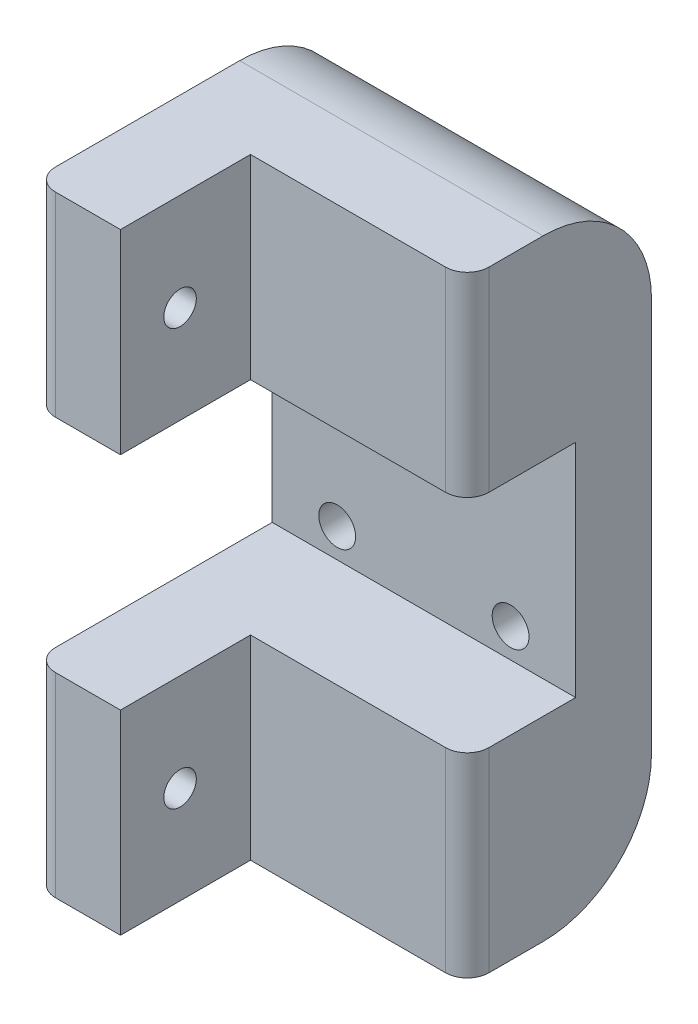
SolidWorks part; units mm, degrees
ref_plane "前视基准面" through (0, 0, 0) normal (0, 0, 1) x (1, 0, 0)
ref_plane "上视基准面" through (0, 0, 0) normal (0, 1, 0) x (1, 0, 0)
ref_plane "右视基准面" through (0, 0, 0) normal (1, 0, 0) x (0, 0, -1)
sketch "草图1" plane through (0, 0, 0) normal (0, 0, 1) x (1, 0, 0)
  line L0 (0, 10.2) -> (30.5146, 10.2) construction
  line L1 (0, 0) -> (28, 0)
  line L2 (0, 0) -> (0, 20.4)
  line L3 (0, 20.4) -> (28, 20.4)
  line L4 (28, 0) -> (28, 20.4)
  line L5 (14, 0) -> (14, 23.8406) construction
  circle A0 centre (6, 2.7) radius 1.5
  circle A1 centre (22, 2.7) radius 1.5
  circle A2 centre (22, 17.7) radius 1.5
  circle A3 centre (6, 17.7) radius 1.5
  point P17 (0, 0)
  point P18 (14, 0)
  dimension "D1" = 3
  dimension "D4" = 20.4
  dimension "D5" = 28
  dimension "D2" = 2
  dimension "D3" = 2
sketch "草图2" plane through (0, 0, 0) normal (0, 0, 1) x (1, 0, 0)
  line L1 (0, 0) -> (28, 0)
  line L2 (0, 0) -> (0, 20.4)
  line L3 (0, 20.4) -> (28, 20.4)
  line L4 (28, 0) -> (28, 20.4)
extrude "凸台-拉伸2" add sketch "草图2" along normal blind 7
sketch "草图5" plane through (0, 20.4, 0) normal (0, 1, 0) x (1, 0, 0)
  line L1 (0, 0) -> (28, 0)
  line L2 (0, 0) -> (0, -17)
  line L3 (0, -17) -> (28, -17)
  line L4 (28, 0) -> (28, -17)
  dimension "D1" = 17
  dimension "D2" = 28
extrude "凸台-拉伸3" add sketch "草图5" along normal blind 18
sketch "草图6" plane through (0, 0, 0) normal (0, -1, 0) x (1, 0, 0)
  line L0 (0, 0) -> (28, 0) construction
  line L1 (0, 17) -> (28, 17)
  line L2 (0, 17) -> (0, 0)
  line L3 (0, 0) -> (28, 0)
  line L4 (28, 17) -> (28, 0)
  dimension "D1" = 28
extrude "凸台-拉伸4" add sketch "草图6" along normal blind 18
hole_wizard "打孔尺寸(%根据十字)槽半沉头木螺钉的类型2" positions "草图7" profile "草图8" countersink size "M3" standard "GB" end condition through all
sketch "草图7" plane through (0, 0, 0) normal (0, 0, -1) x (-1, 0, 0)
  point P0 (-22, 17.7)
  point P3 (-6, 17.7)
  point P6 (-6, 2.7)
  point P9 (-22, 2.7)
sketch "草图8" plane through (22, 17.7, 0) normal (1, 0, 0) x (0, 1, 0)
  line L0 (0, 0) -> (0, 17)
  line L1 (0, 17) -> (1.7, 17)
  line L2 (1.7, 17) -> (1.7, 1.6)
  line L3 (1.7, 1.6) -> (3.3, 0)
  line L5 (3.3, 0) -> (0, 0)
  line L6 (-1.7, 1.6) -> (-3.3, 0) construction
  line L11 (0, -6.35) -> (0, 107.95) construction
  dimension "通孔孔直径" = 3.4
  dimension "通孔孔深度" = 17
  dimension "近端锥形沉头孔直径" = 6.6
  dimension "近端锥形沉头孔角度" = 90
fillet "圆角1" radius 10 2 edges at (14, -18, 0) (14, 38.4, 0)
sketch "草图18" plane through (0, 0, 17) normal (0, 0, 1) x (1, 0, 0)
  line L0 (0, 20.4) -> (28, 20.4) construction
  line L1 (0, 38.4) -> (8, 38.4)
  line L2 (0, 38.4) -> (0, 20.4)
  line L3 (0, 20.4) -> (8, 20.4)
  line L4 (8, 38.4) -> (8, 20.4)
  line L5 (28, -18) -> (0, -18) construction
  line L6 (0, 0) -> (8, 0)
  line L7 (0, 0) -> (0, -18)
  line L8 (0, -18) -> (8, -18)
  line L9 (8, 0) -> (8, -18)
  dimension "D1" = 8
extrude "凸台-拉伸5" add sketch "草图18" along normal blind 12
sketch "草图19" plane through (0, 0, 0) normal (-1, 0, 0) x (0, 0, 1)
  line L0 (29, 38.4) -> (29, 20.4) construction
  line L1 (7, 10.2) -> (25.9499, 10.2) construction
  line L3 (7, 20.4) -> (29, 20.4) construction
  line L4 (0, 28.4) -> (0, -8) construction
  circle A0 centre (23.5, 29.4) radius 1.5
  circle A1 centre (23.5, -9) radius 1.5
  point P8 (0, 0)
  point P11 (0, 0)
  point P12 (22, -11.833)
  point P15 (0, 10.2)
  dimension "D1" = 3
  dimension "D2" = 3
  dimension "D3" = 5.5
  dimension "D4" = 9
extrude "切除-拉伸6" cut sketch "草图19" against normal through all
fillet "圆角2" radius 2 4 edges at (28, 29.4, 17) (28, -9, 17) (0, 29.4, 29) (0, -9, 29)
